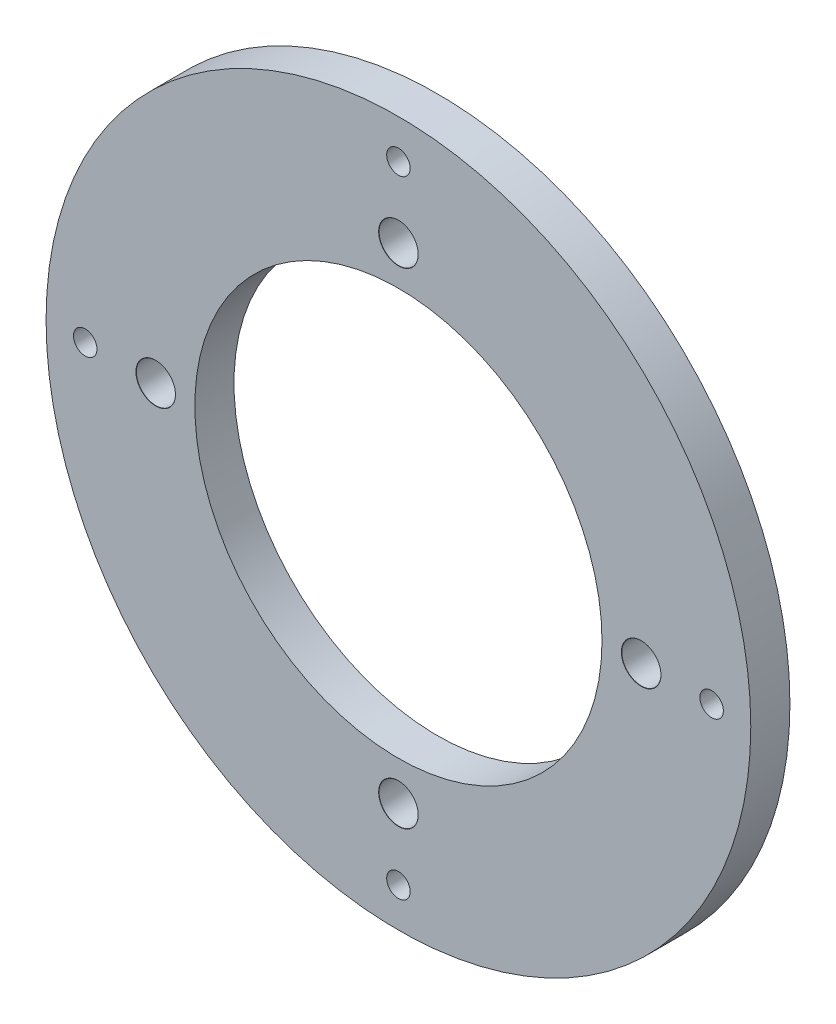
SolidWorks part; units mm, degrees
ref_plane "Front Plane" through (0, 0, 0) normal (0, 0, 1) x (1, 0, 0)
ref_plane "Top Plane" through (0, 0, 0) normal (0, 1, 0) x (1, 0, 0)
ref_plane "Right Plane" through (0, 0, 0) normal (1, 0, 0) x (0, 0, -1)
sketch "Sketch1" plane through (0, 0, 0) normal (0, 0, 1) x (1, 0, 0)
  circle A0 centre (0, 0) radius 26
  circle A1 centre (0, 0) radius 45
  dimension "D1" = 90
  dimension "D2" = 52
extrude "Boss-Extrude1" add sketch "Sketch1" along normal blind 5
hole_wizard "Ø5.0mm Dowel Hole1" positions "Sketch2" profile "Sketch3" hole size "Ø5.0" standard "ISO" end condition through all
sketch "Sketch2" plane through (0, 0, 5) normal (0, 0, 1) x (1, 0, 0)
  line L0 (0, 0) -> (-31.8198, -31.8198) construction
  line L1 (-31.8198, -31.8198) -> (31.8198, 31.8198) construction
  line L2 (31.8198, 31.8198) -> (0, 0) construction
  line L3 (0, 0) -> (31.8198, -31.8198) construction
  line L4 (31.8198, -31.8198) -> (-31.8198, 31.8198) construction
  line L7 (0, 0) -> (-45, 0) construction
  line L8 (-45, 0) -> (45, 0) construction
  line L9 (45, 0) -> (0, 0) construction
  line L10 (0, 0) -> (0, 45) construction
  line L11 (0, 45) -> (0, -45) construction
  circle A0 centre (0, 0) radius 45 construction
  circle A1 centre (0, 0) radius 31
  circle A2 centre (0, 0) radius 40
  point P2 (0, 31)
  point P4 (-31, 0)
  point P6 (0, -31)
  point P8 (31, 0)
  point P55 (0, 0)
  point P56 (0, 0)
  point P57 (0, 0)
  point P58 (0, 0)
  dimension "D1" = 80
  dimension "D2" = 62
sketch "Sketch3" plane through (0, 31, 5) normal (1, 0, 0) x (0, -1, 0)
  line L0 (0, 0) -> (0, 5)
  line L1 (0, 5) -> (2.5, 5)
  line L2 (2.5, 5) -> (2.5, 0.025)
  line L3 (2.5, 0.025) -> (2.525, 0)
  line L5 (2.525, 0) -> (0, 0)
  line L6 (-2.5, 0.025) -> (-2.525, 0) construction
  line L11 (0, -6.35) -> (0, 107.95) construction
  dimension "Thru Hole Dia." = 5
  dimension "Thru Hole Depth" = 5
  dimension "Near C'Sink Dia." = 5.05
  dimension "Near C'Sink Angle" = 90
hole_wizard "Ø3.0mm Dowel Hole3" positions "Sketch11" profile "Sketch12" hole size "Ø3.0" standard "ISO" end condition through all
sketch "Sketch11" plane through (0, 0, 0) normal (0, 0, -1) x (-1, 0, 0)
  line L0 (0, 0) -> (-72.9283, 0) construction
  line L1 (-72.9283, 0) -> (70.6631, 0) construction
  line L2 (70.6631, 0) -> (0, 0) construction
  line L3 (0, 0) -> (0, 47.1297) construction
  line L4 (0, 47.1297) -> (0, -49.2691) construction
  circle A0 centre (0, 0) radius 40
  point P0 (0, 40)
  point P2 (40, 0)
  point P4 (0, -40)
  point P6 (-40, 0)
  point P38 (-40, 0)
  point P39 (0, -40)
  point P40 (40, 0)
  point P41 (0, 40)
  dimension "D1" = 80
sketch "Sketch12" plane through (0, 40, 0) normal (1, 0, 0) x (0, 1, 0)
  line L0 (0, 0) -> (0, 5)
  line L1 (0, 5) -> (1.5, 5)
  line L2 (1.5, 5) -> (1.5, 0.025)
  line L3 (1.5, 0.025) -> (1.525, 0)
  line L5 (1.525, 0) -> (0, 0)
  line L6 (-1.5, 0.025) -> (-1.525, 0) construction
  line L11 (0, -6.35) -> (0, 107.95) construction
  dimension "Thru Hole Dia." = 3
  dimension "Thru Hole Depth" = 5
  dimension "Near C'Sink Dia." = 3.05
  dimension "Near C'Sink Angle" = 90
